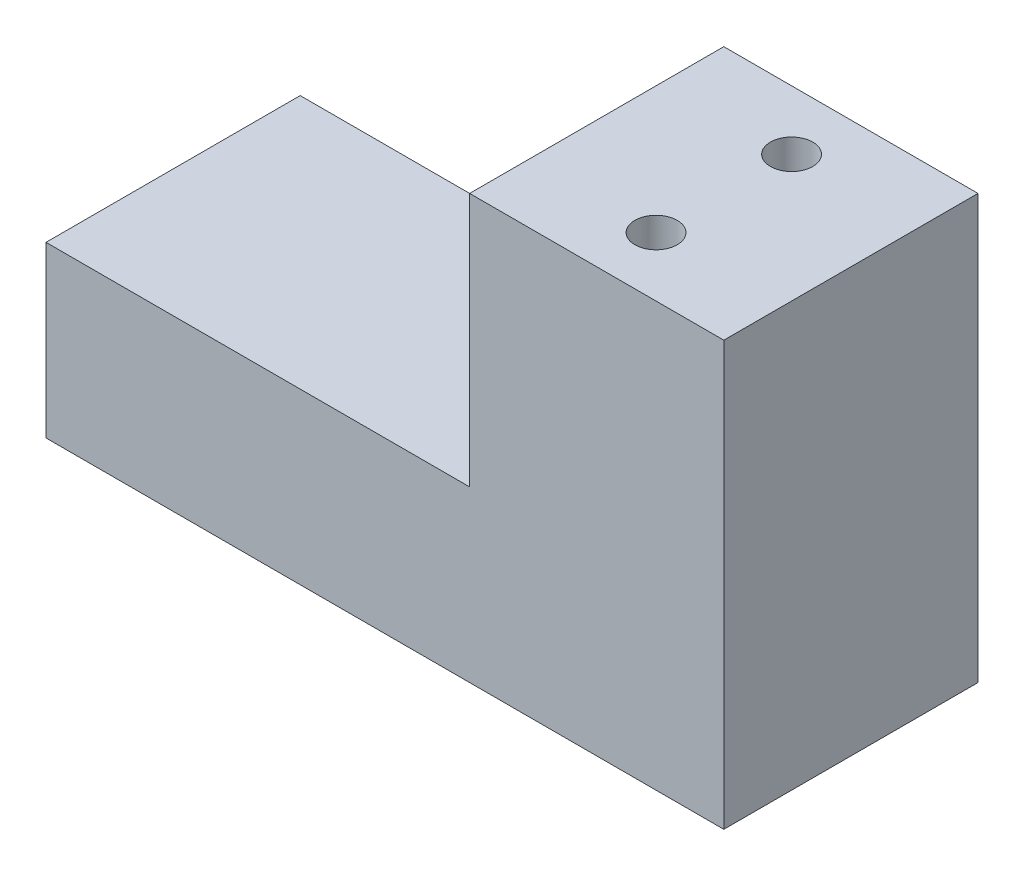
SolidWorks part; units mm, degrees
ref_plane "Front Plane" through (0, 0, 0) normal (0, 0, 1) x (1, 0, 0)
ref_plane "Top Plane" through (0, 0, 0) normal (0, 1, 0) x (1, 0, 0)
ref_plane "Right Plane" through (0, 0, 0) normal (1, 0, 0) x (0, 0, -1)
sketch "Sketch1" plane through (0, 0, 0) normal (0, 0, 1) x (1, 0, 0)
  line L1 (0, 0) -> (80, 0)
  line L2 (0, 0) -> (0, 20)
  line L3 (0, 20) -> (80, 20)
  line L4 (80, 0) -> (80, 20)
  dimension "D1" = 20
  dimension "D2" = 80
extrude "Boss-Extrude1" add sketch "Sketch1" along normal blind 30
sketch "Sketch13" plane through (0, 20, 0) normal (0, 1, 0) x (1, 0, 0)
  line L0 (80, 0) -> (0, 0) construction
  line L1 (80, -30) -> (50, -30)
  line L2 (80, -30) -> (80, 0)
  line L3 (80, 0) -> (50, 0)
  line L4 (50, -30) -> (50, 0)
  dimension "D1" = 30
  dimension "D2" = 30
extrude "Boss-Extrude7" add sketch "Sketch13" along normal blind 30
sketch "Sketch14" plane through (0, 50, 0) normal (0, 1, 0) x (1, 0, 0)
  line L0 (80, 0) -> (50, 0) construction
  circle A0 centre (65, -7) radius 2.5
  circle A1 centre (65, -23) radius 2.5
  point P6 (65, 0)
  dimension "D1" = 5
  dimension "D2" = 16
  dimension "D3" = 7
extrude "Cut-Extrude1" cut sketch "Sketch14" against normal blind 10
